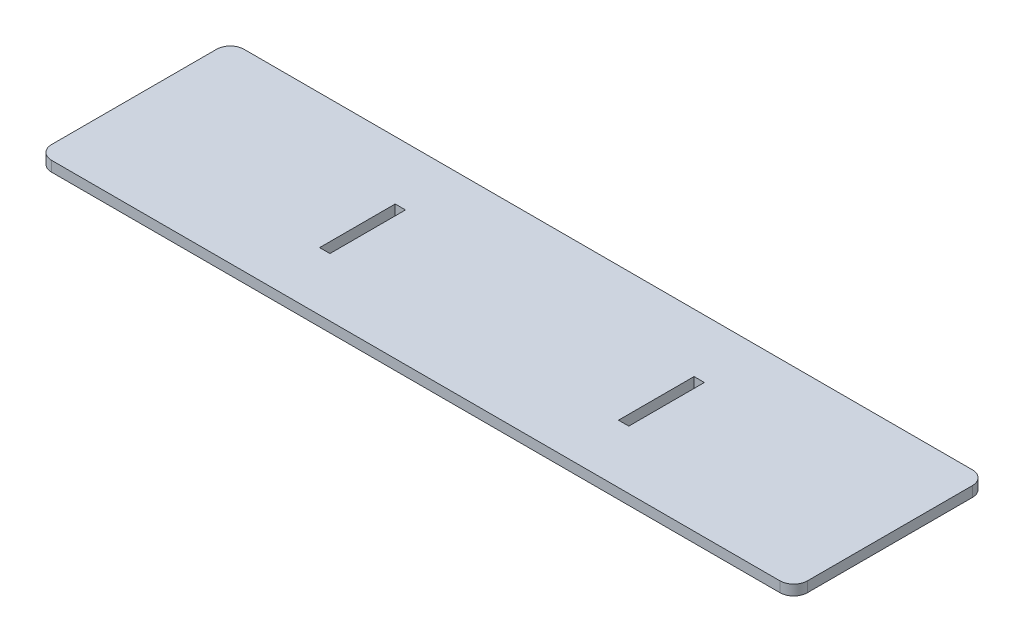
SolidWorks part; units mm, degrees
ref_plane "Front Plane" through (0, 0, 0) normal (0, 0, 1) x (1, 0, 0)
ref_plane "Top Plane" through (0, 0, 0) normal (0, 1, 0) x (1, 0, 0)
ref_plane "Right Plane" through (0, 0, 0) normal (1, 0, 0) x (0, 0, -1)
sketch "Sketch1" plane through (0, 0, 0) normal (0, 1, 0) x (1, 0, 0)
  line L0 (-106, -28) -> (106, -28)
  line L1 (110, -24) -> (110, 24)
  line L2 (106, 28) -> (-106, 28)
  line L3 (-110, 24) -> (-110, -24)
  arc A0 (106, -28) -> (110, -24) centre (106, -24) ccw
  arc A1 (110, 24) -> (106, 28) centre (106, 24) ccw
  arc A2 (-106, 28) -> (-110, 24) centre (-106, 24) ccw
  arc A3 (-110, -24) -> (-106, -28) centre (-106, -24) ccw
extrude "Boss-Extrude1" add sketch "Sketch1" along normal blind 3
sketch "Sketch2" plane through (0, 0, 0) normal (0, 1, 0) x (1, 0, 0)
  line L0 (-45, 11) -> (-42, 11)
  line L1 (-42, 11) -> (-42, -11)
  line L2 (-42, -11) -> (-45, -11)
  line L3 (-45, -11) -> (-45, 11)
  line L4 (42, 11) -> (45, 11)
  line L5 (45, 11) -> (45, -11)
  line L6 (45, -11) -> (42, -11)
  line L7 (42, -11) -> (42, 11)
extrude "Cut-Extrude1" cut sketch "Sketch2" against normal through all and the other way through all
